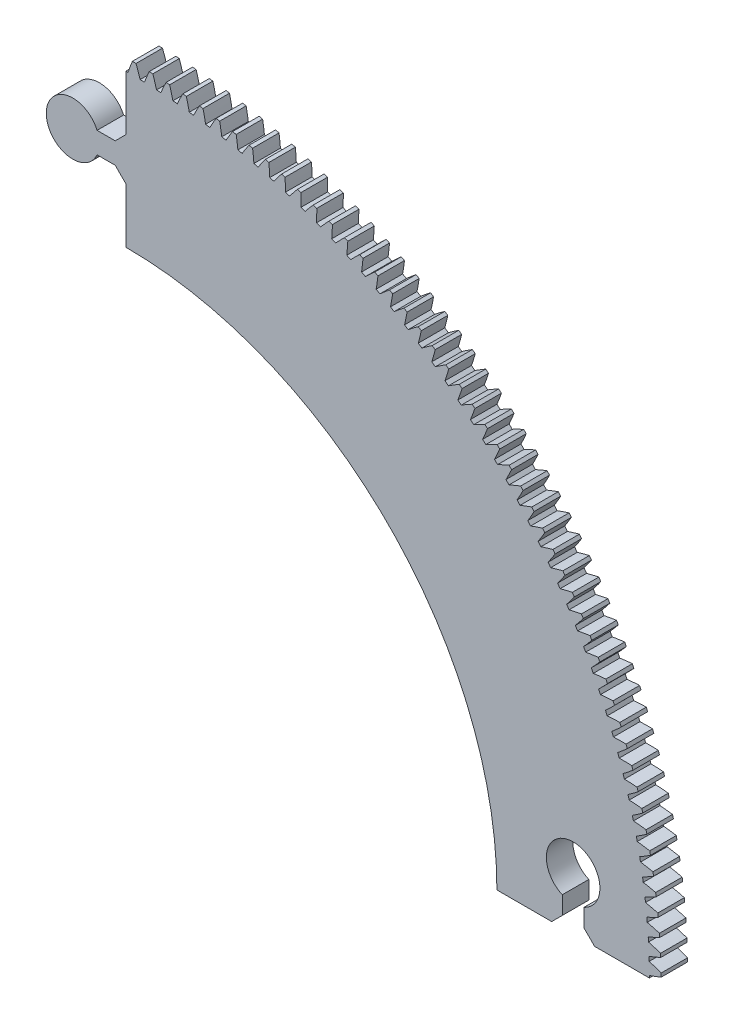
SolidWorks part; units mm, degrees
ref_plane "Front Plane" through (0, 0, 0) normal (0, 0, 1) x (1, 0, 0)
ref_plane "Top Plane" through (0, 0, 0) normal (0, 1, 0) x (1, 0, 0)
ref_plane "Right Plane" through (0, 0, 0) normal (1, 0, 0) x (0, 0, -1)
sketch "Sketch1" plane through (0, 0, 0) normal (0, 0, 1) x (1, 0, 0)
  line L0 (0, 88.9) -> (0, 104.6226)
  line L1 (88.9, 0) -> (104.5591, 0)
  line L2 (0, 107.1626) -> (-12.7, 107.1626) construction
  line L3 (0, 109.7026) -> (-6.8801, 109.7026)
  line L4 (0, 104.6226) -> (-6.8801, 104.6226)
  line L5 (0, 109.7026) -> (0, 125.4252)
  line L6 (0, 109.7026) -> (-12.7, 109.7026) construction
  line L7 (0, 104.6226) -> (-12.7, 104.6226) construction
  line L8 (107.1626, 0) -> (107.1626, 12.7) construction
  line L9 (109.7661, 0) -> (109.7661, 6.8387)
  line L10 (104.5591, 0) -> (104.5591, 6.8387)
  line L11 (109.7661, 0) -> (125.4252, 0)
  line L12 (104.5591, 0) -> (104.5591, 12.7) construction
  line L13 (109.7661, 0) -> (109.7661, 12.7) construction
  arc A0 (88.9, 0) -> (0, 88.9) centre (0, 0) ccw
  arc A1 (-6.8801, 109.7026) -> (-6.8801, 104.6226) centre (-12.7, 107.1626) ccw
  arc A2 (109.7661, 6.8387) -> (104.5591, 6.8387) centre (107.1626, 12.7) ccw
  arc A2012 (125.4252, 0) -> (125.4241, 0.5205) centre (0, 0) ccw
  arc A2013 (125.4241, 0.5205) -> (128.2602, 1.5849) centre (109.0002, 48.5923) ccw
  arc A2014 (128.2602, 1.5849) -> (128.2467, 2.4446) centre (0, 0) ccw
  arc A2015 (128.2467, 2.4446) -> (125.3786, 3.4194) centre (110.4728, -45.1445) ccw
  arc A2016 (125.3786, 3.4194) -> (125.3459, 4.4599) centre (0, 0) ccw
  arc A2017 (125.3459, 4.4599) -> (128.1471, 5.6129) centre (107.4201, 51.9921) ccw
  arc A2018 (128.1471, 5.6129) -> (128.1066, 6.4717) centre (0, 0) ccw
  arc A2019 (128.1066, 6.4717) -> (125.2093, 7.356) centre (111.8363, -41.6522) ccw
  arc A2020 (125.2093, 7.356) -> (125.1439, 8.3949) centre (0, 0) ccw
  arc A2021 (125.1439, 8.3949) -> (127.9076, 9.6353) centre (105.734, 55.3406) ccw
  arc A2022 (127.9076, 9.6353) -> (127.8401, 10.4925) centre (0, 0) ccw
  arc A2023 (127.8401, 10.4925) -> (124.9165, 11.2852) centre (113.0894, -38.1188) ccw
  arc A2024 (124.9165, 11.2852) -> (124.8185, 12.3217) centre (0, 0) ccw
  arc A2025 (124.8185, 12.3217) -> (127.5418, 13.6482) centre (103.9436, 58.6345) ccw
  arc A2026 (127.5418, 13.6482) -> (127.4475, 14.5028) centre (0, 0) ccw
  arc A2027 (127.4475, 14.5028) -> (124.5004, 15.2034) centre (114.231, -34.5478) ccw
  arc A2028 (124.5004, 15.2034) -> (124.3699, 16.2362) centre (0, 0) ccw
  arc A2029 (124.3699, 16.2362) -> (127.0502, 17.6477) centre (102.0505, 61.8705) ccw
  arc A2030 (127.0502, 17.6477) -> (126.929, 18.4989) centre (0, 0) ccw
  arc A2031 (126.929, 18.4989) -> (123.9614, 19.1065) centre (115.2598, -30.9427) ccw
  arc A2032 (123.9614, 19.1065) -> (123.7985, 20.1348) centre (0, 0) ccw
  arc A2033 (123.7985, 20.1348) -> (126.4332, 21.6297) centre (100.0568, 65.0454) ccw
  arc A2034 (126.4332, 21.6297) -> (126.2854, 22.4767) centre (0, 0) ccw
  arc A2035 (126.2854, 22.4767) -> (123.3, 22.9908) centre (116.1748, -27.307) ccw
  arc A2036 (123.3, 22.9908) -> (123.105, 24.0134) centre (0, 0) ccw
  arc A2037 (123.105, 24.0134) -> (125.6914, 25.5904) centre (97.9643, 68.1562) ccw
  arc A2038 (125.6914, 25.5904) -> (125.517, 26.4323) centre (0, 0) ccw
  arc A2039 (125.517, 26.4323) -> (122.517, 26.8524) centre (116.9752, -23.6444) ccw
  arc A2040 (122.517, 26.8524) -> (122.29, 27.8684) centre (0, 0) ccw
  arc A2041 (122.29, 27.8684) -> (124.8255, 29.5258) centre (95.7751, 71.1997) ccw
  arc A2042 (124.8255, 29.5258) -> (124.6248, 30.3619) centre (0, 0) ccw
  arc A2043 (124.6248, 30.3619) -> (121.6131, 30.6875) centre (117.6602, -19.9584) ccw
  arc A2044 (121.6131, 30.6875) -> (121.3542, 31.6959) centre (0, 0) ccw
  arc A2045 (121.3542, 31.6959) -> (123.8365, 33.4321) centre (93.4914, 74.1729) ccw
  arc A2046 (123.8365, 33.4321) -> (123.6096, 34.2615) centre (0, 0) ccw
  arc A2047 (123.6096, 34.2615) -> (120.5892, 34.4924) centre (118.2291, -16.2528) ccw
  arc A2048 (120.5892, 34.4924) -> (120.2988, 35.4921) centre (0, 0) ccw
  arc A2049 (120.2988, 35.4921) -> (122.7253, 37.3054) centre (91.1154, 77.073) ccw
  arc A2050 (122.7253, 37.3054) -> (122.4725, 38.1272) centre (0, 0) ccw
  arc A2051 (122.4725, 38.1272) -> (119.4463, 38.2631) centre (118.6812, -12.5311) ccw
  arc A2052 (119.4463, 38.2631) -> (119.1246, 39.2532) centre (0, 0) ccw
  arc A2053 (119.1246, 39.2532) -> (121.4929, 41.1419) centre (88.6495, 79.897) ccw
  arc A2054 (121.4929, 41.1419) -> (121.2144, 41.9554) centre (0, 0) ccw
  arc A2055 (121.2144, 41.9554) -> (118.1855, 41.9962) centre (119.0163, -8.797) ccw
  arc A2056 (118.1855, 41.9962) -> (117.8328, 42.9757) centre (0, 0) ccw
  arc A2057 (117.8328, 42.9757) -> (120.1407, 44.9378) centre (86.0962, 82.6421) ccw
  arc A2058 (120.1407, 44.9378) -> (119.8368, 45.7421) centre (0, 0) ccw
  arc A2059 (119.8368, 45.7421) -> (116.808, 45.6877) centre (119.2339, -5.0543) ccw
  arc A2060 (116.808, 45.6877) -> (116.4248, 46.6557) centre (0, 0) ccw
  arc A2061 (116.4248, 46.6557) -> (118.6699, 48.6894) centre (83.4578, 85.3056) ccw
  arc A2062 (118.6699, 48.6894) -> (118.3408, 49.4837) centre (0, 0) ccw
  arc A2063 (118.3408, 49.4837) -> (115.3153, 49.3342) centre (119.3338, -1.3066) ccw
  arc A2064 (115.3153, 49.3342) -> (114.9018, 50.2896) centre (0, 0) ccw
  arc A2065 (114.9018, 50.2896) -> (117.082, 52.3928) centre (80.7371, 87.885) ccw
  arc A2066 (117.082, 52.3928) -> (116.7281, 53.1765) centre (0, 0) ccw
  arc A2067 (116.7281, 53.1765) -> (113.7088, 52.932) centre (119.316, 2.4424) ccw
  arc A2068 (113.7088, 52.932) -> (113.2655, 53.874) centre (0, 0) ccw
  arc A2069 (113.2655, 53.874) -> (115.3785, 56.0446) centre (77.9368, 90.3777) ccw
  arc A2070 (115.3785, 56.0446) -> (115.0002, 56.8167) centre (0, 0) ccw
  arc A2071 (115.0002, 56.8167) -> (111.99, 56.4776) centre (119.1804, 6.189) ccw
  arc A2072 (111.99, 56.4776) -> (111.5174, 57.4051) centre (0, 0) ccw
  arc A2073 (111.5174, 57.4051) -> (113.5611, 59.6411) centre (75.0595, 92.7811) ccw
  arc A2074 (113.5611, 59.6411) -> (113.1588, 60.4009) centre (0, 0) ccw
  arc A2075 (113.1588, 60.4009) -> (110.1608, 59.9674) centre (118.9272, 9.9295) ccw
  arc A2076 (110.1608, 59.9674) -> (109.6592, 60.8797) centre (0, 0) ccw
  arc A2077 (109.6592, 60.8797) -> (111.6317, 63.1787) centre (72.1081, 95.093) ccw
  arc A2078 (111.6317, 63.1787) -> (111.2057, 63.9255) centre (0, 0) ccw
  arc A2079 (111.2057, 63.9255) -> (108.2228, 63.398) centre (118.5566, 13.6602) ccw
  arc A2080 (108.2228, 63.398) -> (107.6928, 64.2941) centre (0, 0) ccw
  arc A2081 (107.6928, 64.2941) -> (109.5922, 66.654) centre (69.0856, 97.3111) ccw
  arc A2082 (109.5922, 66.654) -> (109.1429, 67.3871) centre (0, 0) ccw
  arc A2083 (109.1429, 67.3871) -> (106.178, 66.7661) centre (118.069, 17.3774) ccw
  arc A2084 (106.178, 66.7661) -> (105.6202, 67.6451) centre (0, 0) ccw
  arc A2085 (105.6202, 67.6451) -> (107.4444, 70.0635) centre (65.9949, 99.4331) ccw
  arc A2086 (107.4444, 70.0635) -> (106.9724, 70.7821) centre (0, 0) ccw
  arc A2087 (106.9724, 70.7821) -> (104.0284, 70.0683) centre (117.4649, 21.0775) ccw
  arc A2088 (104.0284, 70.0683) -> (103.4433, 70.9293) centre (0, 0) ccw
  arc A2089 (103.4433, 70.9293) -> (105.1907, 73.4038) centre (62.8391, 101.457) ccw
  arc A2090 (105.1907, 73.4038) -> (104.6963, 74.1072) centre (0, 0) ccw
  arc A2091 (104.6963, 74.1072) -> (101.7762, 73.3013) centre (116.7449, 24.7567) ccw
  arc A2092 (101.7762, 73.3013) -> (101.1643, 74.1436) centre (0, 0) ccw
  arc A2093 (101.1643, 74.1436) -> (102.8331, 76.6717) centre (59.6212, 103.3807) ccw
  arc A2094 (102.8331, 76.6717) -> (102.3169, 77.3593) centre (0, 0) ccw
  arc A2095 (102.3169, 77.3593) -> (99.4235, 76.462) centre (115.9097, 28.4116) ccw
  arc A2096 (99.4235, 76.462) -> (98.7855, 77.2846) centre (0, 0) ccw
  arc A2097 (98.7855, 77.2846) -> (100.374, 79.8639) centre (56.3445, 105.2025) ccw
  arc A2098 (100.374, 79.8639) -> (99.8365, 80.5349) centre (0, 0) ccw
  arc A2099 (99.8365, 80.5349) -> (96.9727, 79.5473) centre (114.96, 32.0384) ccw
  arc A2100 (96.9727, 79.5473) -> (96.3092, 80.3494) centre (0, 0) ccw
  arc A2101 (96.3092, 80.3494) -> (97.8159, 82.9773) centre (53.0122, 106.9204) ccw
  arc A2102 (97.8159, 82.9773) -> (97.2575, 83.6311) centre (0, 0) ccw
  arc A2103 (97.2575, 83.6311) -> (94.4262, 82.554) centre (113.897, 35.6335) ccw
  arc A2104 (94.4262, 82.554) -> (93.7378, 83.3349) centre (0, 0) ccw
  arc A2105 (93.7378, 83.3349) -> (95.1613, 86.0089) centre (49.6276, 108.5328) ccw
  arc A2106 (95.1613, 86.0089) -> (94.5826, 86.6448) centre (0, 0) ccw
  arc A2107 (94.5826, 86.6448) -> (91.7866, 85.4793) centre (112.7215, 39.1935) ccw
  arc A2108 (91.7866, 85.4793) -> (91.0739, 86.2382) centre (0, 0) ccw
  arc A2109 (91.0739, 86.2382) -> (92.4127, 88.9555) centre (46.194, 110.0381) ccw
  arc A2110 (92.4127, 88.9555) -> (91.8144, 89.573) centre (0, 0) ccw
  arc A2111 (91.8144, 89.573) -> (89.0563, 88.3202) centre (111.4348, 42.7149) ccw
  arc A2112 (89.0563, 88.3202) -> (88.3202, 89.0563) centre (0, 0) ccw
  arc A2113 (88.3202, 89.0563) -> (89.573, 91.8144) centre (42.7149, 111.4348) ccw
  arc A2114 (89.573, 91.8144) -> (88.9555, 92.4127) centre (0, 0) ccw
  arc A2115 (88.9555, 92.4127) -> (86.2382, 91.0739) centre (110.0381, 46.194) ccw
  arc A2116 (86.2382, 91.0739) -> (85.4793, 91.7866) centre (0, 0) ccw
  arc A2117 (85.4793, 91.7866) -> (86.6448, 94.5826) centre (39.1935, 112.7215) ccw
  arc A2118 (86.6448, 94.5826) -> (86.0089, 95.1613) centre (0, 0) ccw
  arc A2119 (86.0089, 95.1613) -> (83.3349, 93.7378) centre (108.5328, 49.6276) ccw
  arc A2120 (83.3349, 93.7378) -> (82.554, 94.4262) centre (0, 0) ccw
  arc A2121 (82.554, 94.4262) -> (83.6311, 97.2575) centre (35.6335, 113.897) ccw
  arc A2122 (83.6311, 97.2575) -> (82.9773, 97.8159) centre (0, 0) ccw
  arc A2123 (82.9773, 97.8159) -> (80.3494, 96.3092) centre (106.9204, 53.0122) ccw
  arc A2124 (80.3494, 96.3092) -> (79.5473, 96.9727) centre (0, 0) ccw
  arc A2125 (79.5473, 96.9727) -> (80.5349, 99.8365) centre (32.0384, 114.96) ccw
  arc A2126 (80.5349, 99.8365) -> (79.8639, 100.374) centre (0, 0) ccw
  arc A2127 (79.8639, 100.374) -> (77.2846, 98.7855) centre (105.2025, 56.3445) ccw
  arc A2128 (77.2846, 98.7855) -> (76.462, 99.4235) centre (0, 0) ccw
  arc A2129 (76.462, 99.4235) -> (77.3593, 102.3169) centre (28.4116, 115.9097) ccw
  arc A2130 (77.3593, 102.3169) -> (76.6717, 102.8331) centre (0, 0) ccw
  arc A2131 (76.6717, 102.8331) -> (74.1436, 101.1643) centre (103.3807, 59.6212) ccw
  arc A2132 (74.1436, 101.1643) -> (73.3013, 101.7762) centre (0, 0) ccw
  arc A2133 (73.3013, 101.7762) -> (74.1072, 104.6963) centre (24.7567, 116.7449) ccw
  arc A2134 (74.1072, 104.6963) -> (73.4038, 105.1907) centre (0, 0) ccw
  arc A2135 (73.4038, 105.1907) -> (70.9293, 103.4433) centre (101.457, 62.8391) ccw
  arc A2136 (70.9293, 103.4433) -> (70.0683, 104.0284) centre (0, 0) ccw
  arc A2137 (70.0683, 104.0284) -> (70.7821, 106.9724) centre (21.0775, 117.4649) ccw
  arc A2138 (70.7821, 106.9724) -> (70.0635, 107.4444) centre (0, 0) ccw
  arc A2139 (70.0635, 107.4444) -> (67.6451, 105.6202) centre (99.4331, 65.9949) ccw
  arc A2140 (67.6451, 105.6202) -> (66.7661, 106.178) centre (0, 0) ccw
  arc A2141 (66.7661, 106.178) -> (67.3871, 109.1429) centre (17.3774, 118.069) ccw
  arc A2142 (67.3871, 109.1429) -> (66.654, 109.5922) centre (0, 0) ccw
  arc A2143 (66.654, 109.5922) -> (64.2941, 107.6928) centre (97.3111, 69.0856) ccw
  arc A2144 (64.2941, 107.6928) -> (63.398, 108.2228) centre (0, 0) ccw
  arc A2145 (63.398, 108.2228) -> (63.9255, 111.2057) centre (13.6602, 118.5566) ccw
  arc A2146 (63.9255, 111.2057) -> (63.1787, 111.6317) centre (0, 0) ccw
  arc A2147 (63.1787, 111.6317) -> (60.8797, 109.6592) centre (95.093, 72.1081) ccw
  arc A2148 (60.8797, 109.6592) -> (59.9674, 110.1608) centre (0, 0) ccw
  arc A2149 (59.9674, 110.1608) -> (60.4009, 113.1588) centre (9.9295, 118.9272) ccw
  arc A2150 (60.4009, 113.1588) -> (59.6411, 113.5611) centre (0, 0) ccw
  arc A2151 (59.6411, 113.5611) -> (57.4051, 111.5174) centre (92.7811, 75.0595) ccw
  arc A2152 (57.4051, 111.5174) -> (56.4776, 111.99) centre (0, 0) ccw
  arc A2153 (56.4776, 111.99) -> (56.8167, 115.0002) centre (6.189, 119.1804) ccw
  arc A2154 (56.8167, 115.0002) -> (56.0446, 115.3785) centre (0, 0) ccw
  arc A2155 (56.0446, 115.3785) -> (53.874, 113.2655) centre (90.3777, 77.9368) ccw
  arc A2156 (53.874, 113.2655) -> (52.932, 113.7088) centre (0, 0) ccw
  arc A2157 (52.932, 113.7088) -> (53.1765, 116.7281) centre (2.4424, 119.316) ccw
  arc A2158 (53.1765, 116.7281) -> (52.3928, 117.082) centre (0, 0) ccw
  arc A2159 (52.3928, 117.082) -> (50.2896, 114.9018) centre (87.885, 80.7371) ccw
  arc A2160 (50.2896, 114.9018) -> (49.3342, 115.3153) centre (0, 0) ccw
  arc A2161 (49.3342, 115.3153) -> (49.4837, 118.3408) centre (-1.3066, 119.3338) ccw
  arc A2162 (49.4837, 118.3408) -> (48.6894, 118.6699) centre (0, 0) ccw
  arc A2163 (48.6894, 118.6699) -> (46.6557, 116.4248) centre (85.3056, 83.4578) ccw
  arc A2164 (46.6557, 116.4248) -> (45.6877, 116.808) centre (0, 0) ccw
  arc A2165 (45.6877, 116.808) -> (45.7421, 119.8368) centre (-5.0543, 119.2339) ccw
  arc A2166 (45.7421, 119.8368) -> (44.9378, 120.1407) centre (0, 0) ccw
  arc A2167 (44.9378, 120.1407) -> (42.9757, 117.8328) centre (82.6421, 86.0962) ccw
  arc A2168 (42.9757, 117.8328) -> (41.9962, 118.1855) centre (0, 0) ccw
  arc A2169 (41.9962, 118.1855) -> (41.9554, 121.2144) centre (-8.797, 119.0163) ccw
  arc A2170 (41.9554, 121.2144) -> (41.1419, 121.4929) centre (0, 0) ccw
  arc A2171 (41.1419, 121.4929) -> (39.2532, 119.1246) centre (79.897, 88.6495) ccw
  arc A2172 (39.2532, 119.1246) -> (38.2631, 119.4463) centre (0, 0) ccw
  arc A2173 (38.2631, 119.4463) -> (38.1272, 122.4725) centre (-12.5311, 118.6812) ccw
  arc A2174 (38.1272, 122.4725) -> (37.3054, 122.7253) centre (0, 0) ccw
  arc A2175 (37.3054, 122.7253) -> (35.4921, 120.2988) centre (77.073, 91.1154) ccw
  arc A2176 (35.4921, 120.2988) -> (34.4924, 120.5892) centre (0, 0) ccw
  arc A2177 (34.4924, 120.5892) -> (34.2615, 123.6096) centre (-16.2528, 118.2291) ccw
  arc A2178 (34.2615, 123.6096) -> (33.4321, 123.8365) centre (0, 0) ccw
  arc A2179 (33.4321, 123.8365) -> (31.6959, 121.3542) centre (74.1729, 93.4914) ccw
  arc A2180 (31.6959, 121.3542) -> (30.6875, 121.6131) centre (0, 0) ccw
  arc A2181 (30.6875, 121.6131) -> (30.3619, 124.6248) centre (-19.9584, 117.6602) ccw
  arc A2182 (30.3619, 124.6248) -> (29.5258, 124.8255) centre (0, 0) ccw
  arc A2183 (29.5258, 124.8255) -> (27.8684, 122.29) centre (71.1997, 95.7751) ccw
  arc A2184 (27.8684, 122.29) -> (26.8524, 122.517) centre (0, 0) ccw
  arc A2185 (26.8524, 122.517) -> (26.4323, 125.517) centre (-23.6444, 116.9752) ccw
  arc A2186 (26.4323, 125.517) -> (25.5904, 125.6914) centre (0, 0) ccw
  arc A2187 (25.5904, 125.6914) -> (24.0134, 123.105) centre (68.1562, 97.9643) ccw
  arc A2188 (24.0134, 123.105) -> (22.9908, 123.3) centre (0, 0) ccw
  arc A2189 (22.9908, 123.3) -> (22.4767, 126.2854) centre (-27.307, 116.1748) ccw
  arc A2190 (22.4767, 126.2854) -> (21.6297, 126.4332) centre (0, 0) ccw
  arc A2191 (21.6297, 126.4332) -> (20.1348, 123.7985) centre (65.0454, 100.0568) ccw
  arc A2192 (20.1348, 123.7985) -> (19.1065, 123.9614) centre (0, 0) ccw
  arc A2193 (19.1065, 123.9614) -> (18.4989, 126.929) centre (-30.9427, 115.2598) ccw
  arc A2194 (18.4989, 126.929) -> (17.6477, 127.0502) centre (0, 0) ccw
  arc A2195 (17.6477, 127.0502) -> (16.2362, 124.3699) centre (61.8705, 102.0505) ccw
  arc A2196 (16.2362, 124.3699) -> (15.2034, 124.5004) centre (0, 0) ccw
  arc A2197 (15.2034, 124.5004) -> (14.5028, 127.4475) centre (-34.5478, 114.231) ccw
  arc A2198 (14.5028, 127.4475) -> (13.6482, 127.5418) centre (0, 0) ccw
  arc A2199 (13.6482, 127.5418) -> (12.3217, 124.8185) centre (58.6345, 103.9436) ccw
  arc A2200 (12.3217, 124.8185) -> (11.2852, 124.9165) centre (0, 0) ccw
  arc A2201 (11.2852, 124.9165) -> (10.4925, 127.8401) centre (-38.1188, 113.0894) ccw
  arc A2202 (10.4925, 127.8401) -> (9.6353, 127.9076) centre (0, 0) ccw
  arc A2203 (9.6353, 127.9076) -> (8.3949, 125.1439) centre (55.3406, 105.734) ccw
  arc A2204 (8.3949, 125.1439) -> (7.356, 125.2093) centre (0, 0) ccw
  arc A2205 (7.356, 125.2093) -> (6.4717, 128.1066) centre (-41.6522, 111.8363) ccw
  arc A2206 (6.4717, 128.1066) -> (5.6129, 128.1471) centre (0, 0) ccw
  arc A2207 (5.6129, 128.1471) -> (4.4599, 125.3459) centre (51.9921, 107.4201) ccw
  arc A2208 (4.4599, 125.3459) -> (3.4194, 125.3786) centre (0, 0) ccw
  arc A2209 (3.4194, 125.3786) -> (2.4446, 128.2467) centre (-45.1445, 110.4728) ccw
  arc A2210 (2.4446, 128.2467) -> (1.5849, 128.2602) centre (0, 0) ccw
  arc A2211 (1.5849, 128.2602) -> (0.5205, 125.4241) centre (48.5923, 109.0002) ccw
  arc A2212 (0.5205, 125.4241) -> (0, 125.4252) centre (0, 0) ccw
  dimension "D1" = 12.7
  dimension "D2" = 12.7
  dimension "D6" = 12.827
  dimension "D5" = 12.7
  dimension "D3" = 2.54
  dimension "D4" = 2.54
  dimension "D7" = 2.6035
  dimension "D8" = 2.6035
extrude "Boss-Extrude1" add sketch "Sketch1" along normal blind 6.35
chamfer "Chamfer1" distance 2.54 angle 45 4 edges at (0, 109.7026, 3.175) (0, 104.6226, 3.175) (109.7661, 0, 3.175) (104.5591, 0, 3.175)
